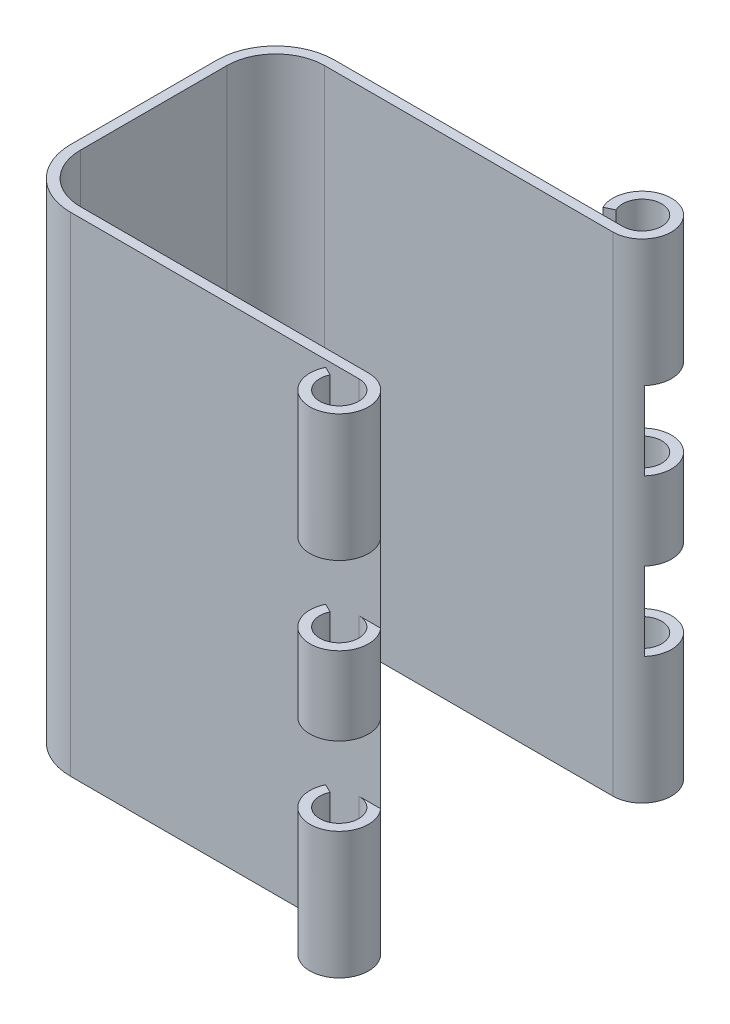
SolidWorks part; units mm, degrees
ref_plane "Front Plane" through (0, 0, 0) normal (0, 0, 1) x (1, 0, 0)
ref_plane "Top Plane" through (0, 0, 0) normal (0, 1, 0) x (1, 0, 0)
ref_plane "Right Plane" through (0, 0, 0) normal (1, 0, 0) x (0, 0, -1)
sketch "Sketch1" plane through (0, 0, 0) normal (0, 1, 0) x (1, 0, 0)
  line L0 (0, 1.905) -> (0, -1.905)
  line L1 (1.27, -3.175) -> (8.763, -3.175)
  line L3 (8.763, 3.175) -> (1.27, 3.175)
  line L4 (9.525, 3.429) -> (9.331, 3.429)
  line L5 (-0.254, 1.905) -> (-0.254, -1.905)
  line L6 (1.27, -3.429) -> (8.763, -3.429)
  line L8 (9.525, -3.429) -> (9.525, 3.429) construction
  line L9 (9.271, -3.175) -> (9.271, 3.175) construction
  line L10 (9.271, 4.505) -> (9.271, 5.3398)
  line L12 (8.763, 3.429) -> (1.27, 3.429)
  line L13 (9.271, 3.175) -> (1.27, 3.175) construction
  line L14 (8.3059, 3.7154) -> (8.0773, 3.6047)
  line L15 (9.525, 3.429) -> (1.27, 3.429) construction
  line L16 (-2.4563, 0) -> (4.7028, 0) construction
  line L17 (8.3059, -3.7154) -> (8.0773, -3.6047)
  line L19 (1.27, -3.175) -> (9.271, -3.175) construction
  line L20 (1.27, -3.429) -> (9.525, -3.429) construction
  arc A0 (0, -1.905) -> (1.27, -3.175) centre (1.27, -1.905) ccw
  arc A1 (1.27, 3.175) -> (0, 1.905) centre (1.27, 1.905) ccw
  arc A2 (1.27, 3.429) -> (-0.254, 1.905) centre (1.27, 1.905) ccw
  arc A3 (-0.254, -1.905) -> (1.27, -3.429) centre (1.27, -1.905) ccw
  arc A4 (8.763, 3.429) -> (8.3059, 3.7154) centre (8.763, 3.937) ccw
  arc A5 (8.763, 3.175) -> (8.0773, 3.6047) centre (8.763, 3.937) ccw
  arc A6 (8.763, -3.429) -> (8.3059, -3.7154) centre (8.763, -3.937) cw
  circle A7 centre (8.763, 3.937) radius 0.762 construction
  circle A8 centre (8.763, 3.937) radius 0.508 construction
  arc A9 (8.763, -3.175) -> (8.0773, -3.6047) centre (8.763, -3.937) cw
  point P22 (9.2488, 4.3561)
  point P27 (9.525, 4.2076)
  dimension "D3" = 1.27
  dimension "D5" = 1.016
  dimension "D1" = 3.175
  dimension "D2" = 9.525
  dimension "D4" = 0.254
  dimension "D6" = 0.254
extrude "Boss-Extrude1" add sketch "Sketch1" along normal blind 12.7 contours A9 L1 A0 L0 A1 L3 A5 L14 A4 L12 A2 L5 A3 L6 A6 L17
sketch "Sketch2" plane through (-0.254, 0, 0) normal (-1, 0, 0) x (0, 0, 1)
  line L0 (-3.429, 12.7) -> (-3.429, 0) construction
  line L1 (-5.9174, 9.398) -> (-3.429, 9.398)
  line L2 (-5.9174, 9.398) -> (-5.9174, 7.366)
  line L3 (-5.9174, 7.366) -> (-3.429, 7.366)
  line L4 (-3.429, 9.398) -> (-3.429, 7.366)
  line L9 (-3.175, 12.7) -> (-4.699, 12.7) construction
  line L11 (-3.429, 3.302) -> (-5.9174, 3.302)
  line L12 (-3.429, 3.302) -> (-3.429, 5.334)
  line L13 (-3.429, 5.334) -> (-5.9174, 5.334)
  line L14 (-5.9174, 3.302) -> (-5.9174, 5.334)
  line L15 (-4.699, 0) -> (-3.175, 0) construction
  dimension "D1" = 3.302
  dimension "D2" = 2.032
  dimension "D3" = 3.302
  dimension "D4" = 2.032
extrude "Cut-Extrude1" cut sketch "Sketch2" against normal blind 12.7
ref_plane "Plane1" through (0, 0, 0) normal (0, 0, -1) x (-1, 0, 0)
mirror "Mirror1" about plane through (0, 0, 0) normal (0, 0, -1) of "Cut-Extrude1"
